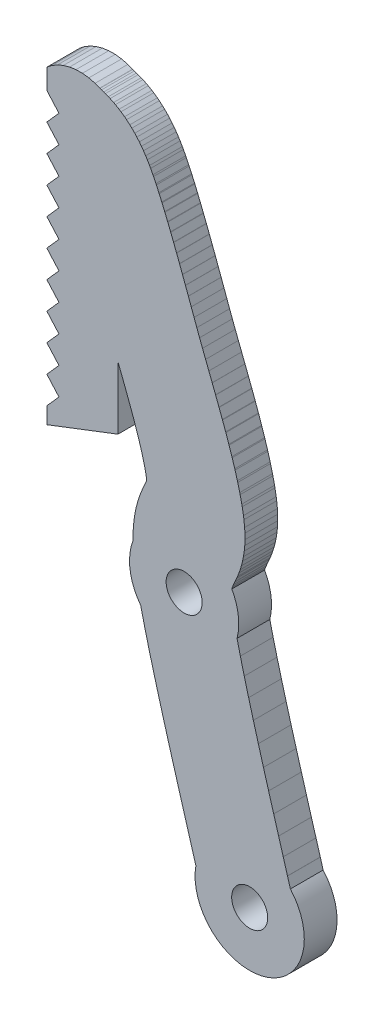
SolidWorks part; units mm, degrees
ref_plane "Спереди" through (0, 0, 0) normal (0, 0, 1) x (1, 0, 0)
ref_plane "Сверху" through (0, 0, 0) normal (0, 1, 0) x (1, 0, 0)
ref_plane "Справа" through (0, 0, 0) normal (1, 0, 0) x (0, 0, -1)
other "Configuration Table"
sketch "Eskiz_kontur" plane through (0, 0, 0) normal (0, 0, 1) x (1, 0, 0)
  line L0 (6.8, 63.7789) -> (0.3, 61.2789)
  line L1 (0.3, 61.2789) -> (0.3, 62.7901)
  line L2 (6.8, 69.5292) -> (6.8, 63.7789)
  line L3 (0.3, 62.7901) -> (1.4, 64.0289)
  line L4 (7.0389, 68.9152) -> (6.8, 69.5292)
  line L5 (1.4, 64.0289) -> (0.3, 65.2676)
  line L6 (7.3397, 68.1369) -> (7.0389, 68.9152)
  line L7 (0.3, 65.2676) -> (0.3, 65.2901)
  line L8 (7.6348, 67.3631) -> (7.3397, 68.1369)
  line L9 (0.3, 65.2901) -> (1.4, 66.5289)
  line L10 (7.9202, 66.5988) -> (7.6348, 67.3631)
  line L11 (1.4, 66.5289) -> (0.3, 67.7676)
  line L12 (8.1924, 65.8491) -> (7.9202, 66.5988)
  line L13 (0.3, 67.7676) -> (0.3, 67.7901)
  line L14 (8.4474, 65.12) -> (8.1924, 65.8491)
  line L15 (0.3, 67.7901) -> (1.4, 69.0289)
  line L16 (8.6813, 64.4177) -> (8.4474, 65.12)
  line L17 (1.4, 69.0289) -> (0.3, 70.2676)
  line L18 (8.8903, 63.7494) -> (8.6813, 64.4177)
  line L19 (0.3, 70.2676) -> (0.3, 70.2901)
  line L20 (9.0708, 63.1233) -> (8.8903, 63.7494)
  line L21 (0.3, 70.2901) -> (1.4, 71.5289)
  line L22 (9.2193, 62.549) -> (9.0708, 63.1233)
  line L23 (1.4, 71.5289) -> (0.3, 72.7676)
  line L24 (9.3329, 62.0382) -> (9.2193, 62.549)
  line L25 (0.3, 72.7676) -> (0.3, 72.7901)
  line L26 (9.4042, 61.6389) -> (9.3329, 62.0382)
  line L27 (0.3, 72.7901) -> (1.4, 74.0289)
  line L28 (9.4275, 61.4254) -> (9.4042, 61.6389)
  line L29 (1.4, 74.0289) -> (0.3, 75.2676)
  line L30 (9.4276, 61.4168) -> (9.4275, 61.4254)
  line L31 (0.3, 75.2676) -> (0.3, 75.2901)
  line L32 (9.3936, 61.3303) -> (9.4276, 61.4168)
  line L33 (0.3, 75.2901) -> (1.4, 76.5289)
  line L34 (9.2834, 61.08) -> (9.3936, 61.3303)
  line L35 (1.4, 76.5289) -> (0.3, 77.7676)
  line L36 (9.1312, 60.7392) -> (9.2834, 61.08)
  line L37 (0.3, 77.7676) -> (0.3, 77.7901)
  line L38 (9.0807, 60.6216) -> (9.1312, 60.7392)
  line L39 (0.3, 77.7901) -> (1.4, 79.0289)
  line L40 (8.9273, 60.2503) -> (9.0807, 60.6216)
  line L41 (1.4, 79.0289) -> (0.3, 80.2676)
  line L42 (8.837, 60.0128) -> (8.9273, 60.2503)
  line L43 (0.3, 80.2676) -> (0.3, 80.2901)
  line L44 (8.6962, 59.6087) -> (8.837, 60.0128)
  line L45 (0.3, 80.2901) -> (1.4, 81.5289)
  line L46 (8.5961, 59.2816) -> (8.6962, 59.6087)
  line L47 (1.4, 81.5289) -> (0.3, 82.7676)
  line L48 (8.4768, 58.8317) -> (8.5961, 59.2816)
  line L49 (0.3, 82.7676) -> (0.3, 82.7901)
  line L50 (8.3938, 58.4535) -> (8.4768, 58.8317)
  line L51 (0.3, 82.7901) -> (1.4, 84.0289)
  line L52 (8.3048, 57.9445) -> (8.3938, 58.4535)
  line L53 (1.4, 84.0289) -> (0.3, 85.2676)
  line L54 (8.254, 57.5542) -> (8.3048, 57.9445)
  line L55 (0.3, 85.2676) -> (0.3, 85.2901)
  line L56 (8.2041, 56.9729) -> (8.254, 57.5542)
  line L57 (0.3, 85.2901) -> (1.4, 86.5289)
  line L58 (8.1877, 56.6011) -> (8.2041, 56.9729)
  line L59 (1.4, 86.5289) -> (0.3, 87.7676)
  line L60 (8.1861, 56.0521) -> (8.1877, 56.6011)
  line L61 (0.3, 87.7676) -> (0.3, 89.6327)
  line L62 (0.3, 89.6327) -> (0.7611, 89.9943)
  line L63 (8.921, 51.0871) -> (8.8864, 51.2454)
  line L64 (0.7611, 89.9943) -> (1.2678, 90.2939)
  line L65 (8.9409, 51.0005) -> (8.921, 51.0871)
  line L66 (1.2678, 90.2939) -> (1.8093, 90.5248)
  line L67 (9.2623, 49.6582) -> (8.9409, 51.0005)
  line L68 (1.8093, 90.5248) -> (2.3762, 90.683)
  line L69 (9.2774, 49.5969) -> (9.2623, 49.6582)
  line L70 (2.3762, 90.683) -> (2.959, 90.7659)
  line L71 (9.6484, 48.1384) -> (9.2774, 49.5969)
  line L72 (2.959, 90.7659) -> (3.5476, 90.772)
  line L73 (9.6602, 48.0931) -> (9.6484, 48.1384)
  line L74 (3.5476, 90.772) -> (4.132, 90.7013)
  line L75 (10.0712, 46.5447) -> (9.6602, 48.0931)
  line L76 (4.132, 90.7013) -> (4.7021, 90.5549)
  line L77 (10.0804, 46.5104) -> (10.0712, 46.5447)
  line L78 (4.7021, 90.5549) -> (5.1292, 90.3832)
  line L79 (10.522, 44.8986) -> (10.0804, 46.5104)
  line L80 (5.1292, 90.3832) -> (5.1546, 90.3757)
  line L81 (10.5293, 44.8721) -> (10.522, 44.8986)
  line L82 (5.1546, 90.3757) -> (5.2968, 90.3325)
  line L83 (10.9918, 43.2232) -> (10.5293, 44.8721)
  line L84 (5.2968, 90.3325) -> (5.4983, 90.2661)
  line L85 (10.9976, 43.2028) -> (10.9918, 43.2232)
  line L86 (5.4983, 90.2661) -> (5.6498, 90.2121)
  line L87 (11.4716, 41.5431) -> (10.9976, 43.2028)
  line L88 (5.6498, 90.2121) -> (5.9236, 90.1044)
  line L89 (11.4761, 41.5275) -> (11.4716, 41.5431)
  line L90 (5.9236, 90.1044) -> (6.0837, 90.0353)
  line L91 (11.952, 39.8835) -> (11.4761, 41.5275)
  line L92 (6.0837, 90.0353) -> (6.4011, 89.8832)
  line L93 (11.9554, 39.8721) -> (11.952, 39.8835)
  line L94 (6.4011, 89.8832) -> (6.569, 89.7946)
  line L95 (12.4237, 38.27) -> (11.9554, 39.8721)
  line L96 (6.569, 89.7946) -> (6.9027, 89.5996)
  line L97 (12.4259, 38.2625) -> (12.4237, 38.27)
  line L98 (6.9027, 89.5996) -> (7.0777, 89.4871)
  line L99 (12.8783, 36.7253) -> (12.4259, 38.2625)
  line L100 (7.0777, 89.4871) -> (7.404, 89.2559)
  line L101 (13.3028, 35.2869) -> (12.8783, 36.7253)
  line L102 (7.404, 89.2559) -> (7.5853, 89.1151)
  line L103 (13.6901, 33.9734) -> (13.3028, 35.2869)
  line L104 (7.5853, 89.1151) -> (7.8865, 88.859)
  line L105 (13.9352, 33.1366) -> (13.6901, 33.9734)
  line L106 (7.8865, 88.859) -> (8.0734, 88.6854)
  line L107 (8.0734, 88.6854) -> (8.3388, 88.4173)
  line L108 (22.3259, 36.5074) -> (22.5884, 35.6116)
  line L109 (8.3388, 88.4173) -> (8.5306, 88.2066)
  line L110 (22.3238, 36.5148) -> (22.3259, 36.5074)
  line L111 (8.5306, 88.2066) -> (8.7564, 87.9383)
  line L112 (21.9349, 37.8339) -> (22.3238, 36.5148)
  line L113 (8.7564, 87.9383) -> (8.9523, 87.6861)
  line L114 (21.5107, 39.2711) -> (21.9349, 37.8339)
  line L115 (8.9523, 87.6861) -> (9.1393, 87.4268)
  line L116 (21.061, 40.7993) -> (21.5107, 39.2711)
  line L117 (9.1393, 87.4268) -> (9.3387, 87.1287)
  line L118 (20.5954, 42.3919) -> (21.061, 40.7993)
  line L119 (9.3387, 87.1287) -> (9.4908, 86.8847)
  line L120 (20.1234, 44.0225) -> (20.5954, 42.3919)
  line L121 (9.4908, 86.8847) -> (9.6928, 86.5363)
  line L122 (19.6545, 45.6641) -> (20.1234, 44.0225)
  line L123 (9.6928, 86.5363) -> (9.7931, 86.3538)
  line L124 (19.1985, 47.2896) -> (19.6545, 45.6641)
  line L125 (9.7931, 86.3538) -> (10.0018, 85.9522)
  line L126 (18.7653, 48.871) -> (19.1985, 47.2896)
  line L127 (10.0018, 85.9522) -> (10.0578, 85.8406)
  line L128 (18.3649, 50.3796) -> (18.7653, 48.871)
  line L129 (10.0578, 85.8406) -> (10.2769, 85.3887)
  line L130 (18.0075, 51.7848) -> (18.3649, 50.3796)
  line L131 (10.2769, 85.3887) -> (10.3176, 85.3025)
  line L132 (17.7061, 53.0435) -> (18.0075, 51.7848)
  line L133 (10.3176, 85.3025) -> (10.5461, 84.8047)
  line L134 (10.5461, 84.8047) -> (10.5766, 84.7368)
  line L135 (17.2517, 56.8099) -> (17.2268, 56.7161)
  line L136 (10.5766, 84.7368) -> (10.8134, 84.1974)
  line L137 (17.2943, 56.9323) -> (17.2517, 56.8099)
  line L138 (10.8134, 84.1974) -> (10.8369, 84.1429)
  line L139 (17.3747, 57.127) -> (17.2943, 56.9323)
  line L140 (10.8369, 84.1429) -> (11.081, 83.5665)
  line L141 (17.5058, 57.4203) -> (17.3747, 57.127)
  line L142 (11.081, 83.5665) -> (11.0995, 83.5221)
  line L143 (17.5155, 57.4424) -> (17.5058, 57.4203)
  line L144 (11.0995, 83.5221) -> (11.3498, 82.9129)
  line L145 (17.6676, 57.7878) -> (17.5155, 57.4424)
  line L146 (11.3498, 82.9129) -> (11.3646, 82.8765)
  line L147 (17.7383, 57.9576) -> (17.6676, 57.7878)
  line L148 (11.3646, 82.8765) -> (11.62, 82.2391)
  line L149 (17.8765, 58.3099) -> (17.7383, 57.9576)
  line L150 (11.62, 82.2391) -> (11.6319, 82.2091)
  line L151 (17.9853, 58.62) -> (17.8765, 58.3099)
  line L152 (11.6319, 82.2091) -> (11.8914, 81.5477)
  line L153 (18.1008, 58.9924) -> (17.9853, 58.62)
  line L154 (11.8914, 81.5477) -> (11.901, 81.523)
  line L155 (18.2094, 59.4134) -> (18.1008, 58.9924)
  line L156 (11.901, 81.523) -> (12.1636, 80.8421)
  line L157 (18.2934, 59.8189) -> (18.2094, 59.4134)
  line L158 (12.1636, 80.8421) -> (12.1714, 80.8219)
  line L159 (18.3661, 60.2993) -> (18.2934, 59.8189)
  line L160 (12.1714, 80.8219) -> (12.436, 80.1259)
  line L161 (18.4096, 60.7512) -> (18.3661, 60.2993)
  line L162 (12.436, 80.1259) -> (12.4421, 80.1095)
  line L163 (18.4301, 61.2328) -> (18.4096, 60.7512)
  line L164 (12.4421, 80.1095) -> (12.7077, 79.4027)
  line L165 (18.4245, 61.7443) -> (18.4301, 61.2328)
  line L166 (12.7077, 79.4027) -> (12.7125, 79.3898)
  line L167 (18.3983, 62.1823) -> (18.4245, 61.7443)
  line L168 (12.7125, 79.3898) -> (12.9779, 78.6766)
  line L169 (18.3346, 62.7666) -> (18.3983, 62.1823)
  line L170 (12.9779, 78.6766) -> (12.9816, 78.6668)
  line L171 (18.2911, 63.0697) -> (18.3346, 62.7666)
  line L172 (12.9816, 78.6668) -> (13.2458, 77.9517)
  line L173 (18.1761, 63.7135) -> (18.2911, 63.0697)
  line L174 (13.2458, 77.9517) -> (13.2484, 77.9448)
  line L175 (18.1388, 63.9) -> (18.1761, 63.7135)
  line L176 (13.2484, 77.9448) -> (13.5104, 77.2322)
  line L177 (17.9878, 64.5784) -> (18.1388, 63.9)
  line L178 (13.5104, 77.2322) -> (13.7706, 76.5224)
  line L179 (17.952, 64.7275) -> (17.9878, 64.5784)
  line L180 (13.7706, 76.5224) -> (14.0214, 75.8376)
  line L181 (17.7688, 65.4362) -> (17.952, 64.7275)
  line L182 (14.0214, 75.8376) -> (14.2727, 75.1625)
  line L183 (17.7359, 65.5562) -> (17.7688, 65.4362)
  line L184 (14.2727, 75.1625) -> (14.5404, 74.4599)
  line L185 (17.5242, 66.2908) -> (17.7359, 65.5562)
  line L186 (14.5404, 74.4599) -> (14.8253, 73.7231)
  line L187 (17.495, 66.388) -> (17.5242, 66.2908)
  line L188 (14.8253, 73.7231) -> (15.1231, 72.9581)
  line L189 (17.2585, 67.1441) -> (17.495, 66.388)
  line L190 (15.1231, 72.9581) -> (15.4281, 72.1743)
  line L191 (17.2331, 67.2227) -> (17.2585, 67.1441)
  line L192 (15.4281, 72.1743) -> (15.4319, 72.1645)
  line L193 (16.9756, 67.9959) -> (17.2331, 67.2227)
  line L194 (15.4319, 72.1645) -> (15.7383, 71.3718)
  line L195 (16.954, 68.0592) -> (16.9756, 67.9959)
  line L196 (15.7383, 71.3718) -> (15.7456, 71.3527)
  line L197 (16.6792, 68.8451) -> (16.954, 68.0592)
  line L198 (15.7456, 71.3527) -> (16.0497, 70.5551)
  line L199 (16.6612, 68.8953) -> (16.6792, 68.8451)
  line L200 (16.0497, 70.5551) -> (16.0605, 70.5265)
  line L201 (16.3729, 69.6895) -> (16.6612, 68.8953)
  line L202 (16.0605, 70.5265) -> (16.3586, 69.7284)
  line L203 (16.3586, 69.7284) -> (16.3729, 69.6895)
  arc A0 (8.8864, 51.2454) -> (8.1861, 56.0521) centre (12.8611, 54.2789) cw
  arc A1 (22.5884, 35.6116) -> (13.9352, 33.1366) centre (18.8611, 32.2789) cw
  arc A2 (17.2268, 56.7161) -> (17.7061, 53.0435) centre (12.8611, 54.2789) cw
extrude "Plastina" add sketch "Eskiz_kontur" along normal blind 3
sketch "Eskiz_otverstiya" plane through (0, 0, 0) normal (0, 0, 1) x (1, 0, 0)
  circle A0 centre (18.8611, 32.2789) radius 1.65
  circle A1 centre (12.8611, 54.2789) radius 1.65
  dimension "d1" = 3.3
  dimension "d2" = 3.3
extrude "Otverstiya" cut sketch "Eskiz_otverstiya" against normal through all and the other way through all
equation "\"T3\" = 3"
equation "\"T5\" = 5"
equation "\"D_M3\" = 3.3"
equation "\"D_M2\" = 2.2"
equation "\"D_M3_TAP\" = 2.5"
equation "\"D_M4\" = 4.5"
equation "\"L1\" = 100"
equation "\"L2\" = 100"
equation "\"D1@Plastina\" = \"T3\""
equation "\"d1@Eskiz_otverstiya\" = \"D_M3\""
equation "\"d2@Eskiz_otverstiya\" = \"D_M3\""
